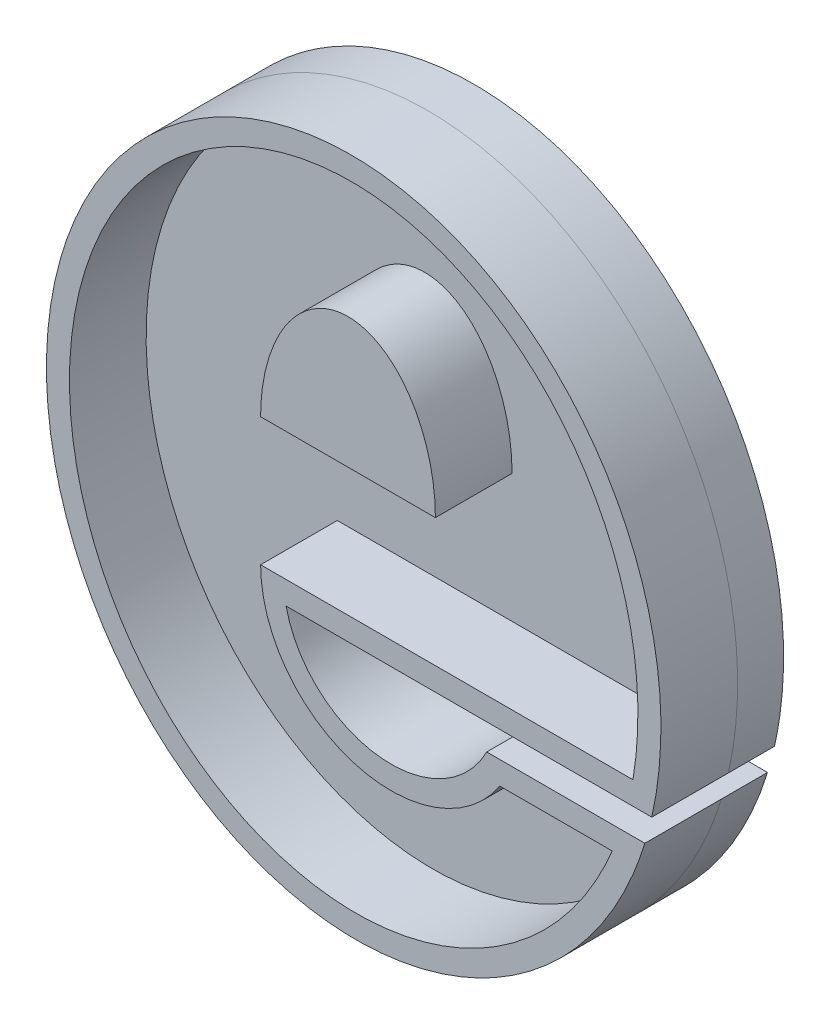
SolidWorks part; units mm, degrees
ref_plane "Alzado" through (0, 0, 0) normal (0, 0, 1) x (1, 0, 0)
ref_plane "Planta" through (0, 0, 0) normal (0, 1, 0) x (1, 0, 0)
ref_plane "Vista lateral" through (0, 0, 0) normal (1, 0, 0) x (0, 0, -1)
sketch "Sketch1" plane through (0, 0, 0) normal (0, 0, 1) x (1, 0, 0)
  line L0 (-6.0711, -4.0155) -> (18.2111, -4.0155)
  line L1 (9.5333, -8.7155) -> (16.8586, -8.7155)
  line L2 (-4.4087, -5.5155) -> (19.4413, -5.5155)
  line L3 (8.6759, -7.2155) -> (18.9888, -7.2155)
  arc A0 (-6.0711, -4.0155) -> (9.5333, -8.7155) centre (2.4389, -4.0155) ccw
  arc A1 (-4.4087, -5.5155) -> (8.6759, -7.2155) centre (2.4389, -4.0155) ccw
  ellipse E0 centre (0, 0) end of major axis (-0.7987, 20.5745) minor radius 18.535 (18.2111, -4.0155) -> (16.8586, -8.7155) ccw
  spline S0 degree 1 poles (19.4413, -5.5155) (18.9888, -7.2155) knots 0 0 1 1 construction
  spline S1 degree 3 poles (19.4413, -5.5155) (20.0645, -2.7694) (20.3372, 2.995) (17.7717, 11.2083) (12.5782, 17.8057) (5.4743, 21.7911) (-2.4911, 22.5104) (-10.0691, 19.8325) (-16.0956, 14.2106) (-19.7131, 6.5261) (-20.4358, -2.0917) (-18.1711, -10.408) (-13.2243, -17.2246) (-6.2758, -21.5205) (1.6565, -22.5965) (9.3333, -20.2624) (14.5284, -15.7997) (17.5172, -11.1566) (18.5805, -8.5474) (18.9888, -7.2155) knots -1.860254 -1.860254 -1.860254 -1.860254 -1.472609 -1.084963 -0.697318 -0.309673 0.077973 0.465618 0.853263 1.240908 1.628554 2.016199 2.403844 2.791489 3.179135 3.56678 3.954425 4.148248 4.342071 4.342071 4.342071 4.342071
  point P10 (2.4389, -4.0155)
  point P13 (18.2111, -4.0155)
  point P15 (2.425, -8.7)
  point P16 (2.425, -8.7)
  point P17 (0, 0)
  point P18 (7.1637, -8.7155)
  point P19 (9.5333, -8.7155)
  point P20 (0, 0)
  point P21 (0, 0)
  point P22 (0, 0)
  point P23 (-0.7987, 20.5745)
  point P24 (21.7175, -1.2517)
  dimension "D5" = 8.51
  dimension "D1" = 20.59
  dimension "D2" = 18.535
  dimension "D3" = 24.59
  dimension "D4" = 12.45
  dimension "D6" = 4.7
  dimension "D7" = 1.5
extrude "Boss-Extrude2" add sketch "Sketch1" along normal blind 5
sketch "Sketch4" plane through (0, 0, 0) normal (0, 0, -1) x (-1, 0, 0)
  line L0 (-18.2111, -4.0155) -> (6.0711, -4.0155) construction
  line L1 (-16.8586, -8.7155) -> (-9.5333, -8.7155) construction
  line L2 (-19.4413, -5.5155) -> (4.4087, -5.5155)
  line L3 (-18.9888, -7.2155) -> (-8.6759, -7.2155)
  arc A0 (-9.5333, -8.7155) -> (6.0711, -4.0155) centre (-2.4389, -4.0155) ccw construction
  arc A1 (-8.6759, -7.2155) -> (4.4087, -5.5155) centre (-2.4389, -4.0155) ccw
  ellipse E0 centre (0, 0) end of major axis (0.7987, 20.5745) minor radius 18.535 (-16.8586, -8.7155) -> (-18.2111, -4.0155) ccw construction
  ellipse E1 centre (0, 0) end of major axis (0.7987, 20.5745) minor radius 18.535 (-16.8586, -8.7155) -> (-18.2111, -4.0155) ccw construction
  spline S0 degree 1 poles (-18.9888, -7.2155) (-19.4413, -5.5155) knots 0 0 1 1 construction
  spline S1 degree 3 poles (-18.9888, -7.2155) (-18.5805, -8.5474) (-17.5172, -11.1566) (-14.5284, -15.7997) (-9.3333, -20.2624) (-1.6565, -22.5965) (6.2758, -21.5205) (13.2243, -17.2246) (18.1711, -10.408) (20.4358, -2.0917) (19.7131, 6.5261) (16.0956, 14.2106) (10.0691, 19.8325) (2.4911, 22.5104) (-5.4743, 21.7911) (-12.5782, 17.8057) (-17.7717, 11.2083) (-20.3372, 2.995) (-20.0645, -2.7694) (-19.4413, -5.5155) knots 1.941115 1.941115 1.941115 1.941115 2.134937 2.32876 2.716405 3.104051 3.491696 3.879341 4.266986 4.654632 5.042277 5.429922 5.817568 6.205213 6.592858 6.980503 7.368149 7.755794 8.143439 8.143439 8.143439 8.143439
  point P2 (-76.7854, -11.4612)
  dimension "D1" = 1.5
extrude "Boss-Extrude3" add sketch "Sketch4" along normal blind 3
sketch "Sketch3" plane through (0, 0, 5) normal (0, 0, 1) x (1, 0, 0)
  line L1 (-6.0711, -4.0155) -> (18.2111, -4.0155) construction
  line L2 (-6.0711, 4.3445) -> (5.3289, 4.3445)
  ellipse E0 centre (0, 0) end of major axis (-0.7987, 20.5745) minor radius 18.535 (18.2111, -4.0155) -> (16.8586, -8.7155) ccw construction
  ellipse E1 centre (-0.3711, 4.3445) end of major axis (-0.3711, 12.8545) minor radius 5.7 (5.3289, 4.3445) -> (-6.0711, 4.3445) ccw
  point P1 (0, 0)
  point P2 (0, 0)
  point P7 (0, 0)
  point P8 (0, 0)
  point P10 (18.1296, 4.1345)
  point P18 (0, 4.1345)
  point P21 (-1.6222, 12.9493)
  point P24 (0, 0)
  point P25 (0, 0)
  dimension "D2" = 8.51
  dimension "D3" = 8.36
  dimension "D1" = 11.4
extrude "Boss-Extrude4" add sketch "Sketch3" against normal blind 8
